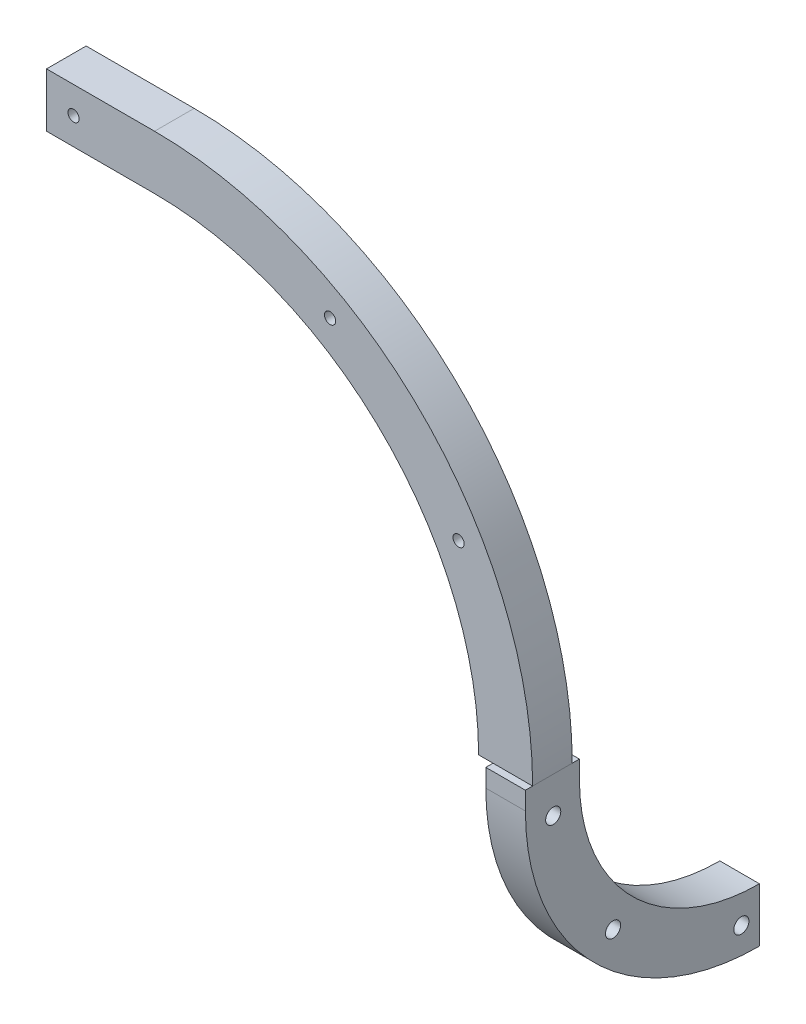
SolidWorks part; units mm, degrees
material "ABS"
ref_plane "前视基准面" through (0, 0, 0) normal (0, 0, 1) x (1, 0, 0)
ref_plane "上视基准面" through (0, 0, 0) normal (0, 1, 0) x (1, 0, 0)
ref_plane "右视基准面" through (0, 0, 0) normal (1, 0, 0) x (0, 0, -1)
other "Configuration Table"
sketch "草图1" plane through (0, 0, 0) normal (0, 0, 1) x (1, 0, 0)
  line L0 (0, 105) -> (0, 0) construction
  line L1 (0, 0) -> (105, 0) construction
  line L2 (90, 0) -> (105, 0)
  line L3 (0, 105) -> (0, 90)
  arc A0 (0, 105) -> (105, 0) centre (0, 0) cw
  arc A1 (0, 90) -> (90, 0) centre (0, 0) cw
  dimension "D1" = 105
  dimension "D2" = 90
extrude "凸台-拉伸1" add sketch "草图1" along normal blind 15
sketch "草图2" plane through (0, 0, 0) normal (0, -1, 0) x (1, 0, 0)
  line L1 (90, 15) -> (105, 15)
  line L2 (90, 15) -> (90, 0)
  line L3 (90, 0) -> (105, 0)
  line L4 (105, 15) -> (105, 0)
extrude "凸台-拉伸2" add sketch "草图2" along normal blind 5
sketch "草图3" plane through (105, 0, 0) normal (1, 0, 0) x (0, 0, -1)
  line L0 (0, -5) -> (50, -5) construction
  line L1 (50, -5) -> (50, -55) construction
  line L2 (50, -55) -> (50, -70)
  line L3 (-15, -5) -> (0, -5)
  arc A0 (0, -5) -> (50, -55) centre (50, -5) ccw
  arc A1 (-15, -5) -> (50, -70) centre (50, -5) ccw
  dimension "D1" = 50
extrude "凸台-拉伸3" add sketch "草图3" against normal blind 15
sketch "草图4" plane through (0, 0, 15) normal (0, 0, 1) x (1, 0, 0)
  line L0 (25.2349, 94.1778) -> (0, 0) construction
  line L1 (0, 0) -> (68.9429, 68.9429) construction
  line L2 (0, 0) -> (94.1778, 25.2349) construction
  line L3 (0, 0) -> (90, 0) construction
  line L4 (48.75, 84.4375) -> (0, 0) construction
  line L5 (84.4375, 48.75) -> (0, 0) construction
  arc A0 (10.4903, 96.934) -> (39.3822, 89.1925) centre (0, 0) cw construction
  arc A1 (40.5939, 91.9368) -> (10.813, 99.9166) centre (0, 0) ccw construction
  arc A2 (38.1704, 86.4481) -> (10.1675, 93.9514) centre (0, 0) ccw construction
  arc A3 (38.1704, 86.4481) -> (40.5939, 91.9368) centre (39.3822, 89.1925) ccw construction
  arc A4 (10.813, 99.9166) -> (10.1675, 93.9514) centre (10.4903, 96.934) ccw construction
  arc A5 (57.5518, 78.7022) -> (78.7022, 57.5518) centre (0, 0) cw construction
  arc A6 (81.1238, 59.3227) -> (59.3227, 81.1238) centre (0, 0) ccw construction
  arc A7 (76.2806, 55.781) -> (55.781, 76.2806) centre (0, 0) ccw construction
  arc A8 (76.2806, 55.781) -> (81.1238, 59.3227) centre (78.7022, 57.5518) ccw construction
  arc A9 (59.3227, 81.1238) -> (55.781, 76.2806) centre (57.5518, 78.7022) ccw construction
  arc A10 (89.1925, 39.3822) -> (96.934, 10.4903) centre (0, 0) cw construction
  arc A11 (99.9166, 10.813) -> (91.9368, 40.5939) centre (0, 0) ccw construction
  arc A12 (93.9514, 10.1675) -> (86.4481, 38.1704) centre (0, 0) ccw construction
  arc A13 (93.9514, 10.1675) -> (99.9166, 10.813) centre (96.934, 10.4903) ccw construction
  arc A14 (91.9368, 40.5939) -> (86.4481, 38.1704) centre (89.1925, 39.3822) ccw construction
  circle A17 centre (84.4375, 48.75) radius 1.55
  circle A18 centre (48.75, 84.4375) radius 1.55
  point P4 (25.2349, 94.1778)
  point P9 (68.9429, 68.9429)
  point P18 (94.1778, 25.2349)
  dimension "D1" = 3
  dimension "D2" = 3
  dimension "D3" = 3
  dimension "D7" = 97.5
  dimension "D8" = 97.5
  dimension "D9" = 97.5
  dimension "D12" = 3.1
  dimension "D13" = 3.1
  dimension "D14" = 15
  dimension "D4" = 15
  dimension "D5" = 45
  dimension "D6" = 75
  dimension "D10" = 97.5
  dimension "D11" = 97.5
  dimension "D15" = 15
  dimension "D16" = 15
  dimension "D17" = 15
  dimension "D18" = 15
sketch "草图5" plane through (105, 0, 0) normal (1, 0, 0) x (0, 0, -1)
  line L0 (-2.1127, -29.3006) -> (50, -5) construction
  line L1 (50, -5) -> (25.6994, -57.1127) construction
  line L2 (50, -55) -> (50, -5) construction
  line L3 (50, -5) -> (0, -5) construction
  line L4 (-7.2812, -10.0115) -> (50, -5) construction
  line L5 (50, -5) -> (9.3414, -45.6586) construction
  line L6 (50, -5) -> (44.9694, -62.5) construction
  arc A0 (-5.5348, -19.9043) -> (2.8856, -37.9618) centre (50, -5) ccw construction
  arc A1 (-8.4322, -20.6819) -> (0.4274, -39.6816) centre (50, -5) ccw construction
  arc A2 (-2.6373, -19.1267) -> (5.3437, -36.2421) centre (50, -5) ccw construction
  arc A3 (-2.6373, -19.1267) -> (-8.4322, -20.6819) centre (-5.5348, -19.9043) ccw construction
  arc A4 (0.4274, -39.6816) -> (5.3437, -36.2421) centre (2.8856, -37.9618) ccw construction
  arc A5 (17.0382, -52.1144) -> (35.0957, -60.5348) centre (50, -5) ccw construction
  arc A6 (15.3184, -54.5726) -> (34.3181, -63.4322) centre (50, -5) ccw construction
  arc A7 (18.7579, -49.6563) -> (35.8733, -57.6373) centre (50, -5) ccw construction
  arc A8 (18.7579, -49.6563) -> (15.3184, -54.5726) centre (17.0382, -52.1144) ccw construction
  arc A9 (34.3181, -63.4322) -> (35.8733, -57.6373) centre (35.0957, -60.5348) ccw construction
  circle A13 centre (44.9694, -62.5) radius 1.55
  circle A14 centre (9.3414, -45.6586) radius 1.55
  circle A15 centre (-7.2812, -10.0115) radius 1.55
  point P4 (-2.1127, -29.3006)
  point P9 (25.6994, -57.1127)
  dimension "D1" = 57.5
  dimension "D2" = 57.5
  dimension "D8" = 3.1
  dimension "D9" = 3.1
  dimension "D10" = 3.1
  dimension "D12" = 25
  dimension "D13" = 3
  dimension "D16" = 3
  dimension "D3" = 57.5
  dimension "D4" = 57.5
  dimension "D5" = 57.5
  dimension "D6" = 10
  dimension "D7" = 10
  dimension "D11" = 45
  dimension "D14" = 5
  dimension "D15" = 5
  dimension "D17" = 25
extrude "切除-拉伸1" cut sketch "草图4" against normal through all
extrude "切除-拉伸2" cut sketch "草图5" against normal through all
sketch "草图6" plane through (105, 0, 0) normal (1, 0, 0) x (0, 0, -1)
  line L0 (50, -55) -> (50, -70)
  line L1 (0, -5) -> (-15, -5)
  arc A0 (0, -5) -> (50, -55) centre (50, -5) ccw
  arc A1 (-15, -5) -> (50, -70) centre (50, -5) ccw
extrude "切除-拉伸3" [suppressed] cut sketch "草图6" against normal blind 2
sketch "草图7" plane through (0, 0, 15) normal (0, 0, 1) x (1, 0, 0)
  line L0 (0, 105) -> (0, 90)
  line L1 (90, 0) -> (105, 0)
  line L2 (90, -5) -> (90, 0) construction
  arc A0 (0, 90) -> (90, 0) centre (0, 0) cw
  arc A1 (0, 105) -> (105, 0) centre (0, 0) cw
extrude "切除-拉伸4" cut sketch "草图7" against normal blind 2
sketch "草图8" plane through (90, 0, 0) normal (-1, 0, 0) x (0, 0, 1)
  line L0 (-50, -55) -> (-50, -70)
  line L1 (0, -5) -> (15, -5)
  arc A0 (-50, -55) -> (0, -5) centre (-50, -5) ccw
  arc A1 (-50, -55) -> (0, -5) centre (-50, -5) ccw construction
  arc A2 (-50, -70) -> (15, -5) centre (-50, -5) ccw
extrude "切除-拉伸5" cut sketch "草图8" against normal blind 4
sketch "草图10" plane through (0, 0, 0) normal (0, 0, 1) x (1, 0, 0)
  line L0 (0, 105) -> (0, 90)
  line L1 (90, 0) -> (105, 0)
  arc A0 (0, 90) -> (90, 0) centre (0, 0) cw
  arc A1 (0, 105) -> (105, 0) centre (0, 0) cw
extrude "切除-拉伸6" cut sketch "草图10" along normal blind 2
sketch "草图9" plane through (0, 0, 0) normal (-1, 0, 0) x (0, 0, 1)
  line L0 (13, 105) -> (2, 105) construction
  line L5 (2, 105) -> (13, 105)
  line L6 (2, 105) -> (2, 90)
  line L7 (2, 90) -> (13, 90)
  line L8 (13, 105) -> (13, 90)
  line L9 (13, 90) -> (2, 90) construction
  line L12 (13, 105) -> (2, 105) construction
extrude "凸台-拉伸4" add sketch "草图9" along normal blind 30
sketch "草图11" plane through (90, 0, 0) normal (-1, 0, 0) x (0, 0, 1)
  line L1 (0, 0) -> (15, 0)
  line L2 (0, 0) -> (0, -5)
  line L3 (0, -5) -> (15, -5)
  line L4 (15, 0) -> (15, -5)
extrude "切除-拉伸7" cut sketch "草图11" against normal up to surface (4 mm away) up to face at (94, -39.7043, -15.2957)
sketch "草图12" plane through (105, 0, 0) normal (1, 0, 0) x (0, 0, -1)
  circle A0 centre (-7.2812, -10.0115) radius 2.1
  circle A1 centre (9.3414, -45.6586) radius 2.1
  circle A2 centre (44.9694, -62.5) radius 2.1
  dimension "D1" = 4.2
  dimension "D2" = 4.2
  dimension "D3" = 4.2
extrude "切除-拉伸8" cut sketch "草图12" against normal blind 4.5
sketch "草图13" plane through (0, 0, 13) normal (0, 0, 1) x (1, 0, 0)
  line L0 (-30, 90) -> (0, 90) construction
  line L1 (-30, 90) -> (-30, 105) construction
  circle A0 centre (-22.5, 97.5) radius 1.55
  dimension "D2" = 3.1
  dimension "D1" = 7.5
  dimension "D3" = 7.5
extrude "切除-拉伸9" cut sketch "草图13" against normal through all
